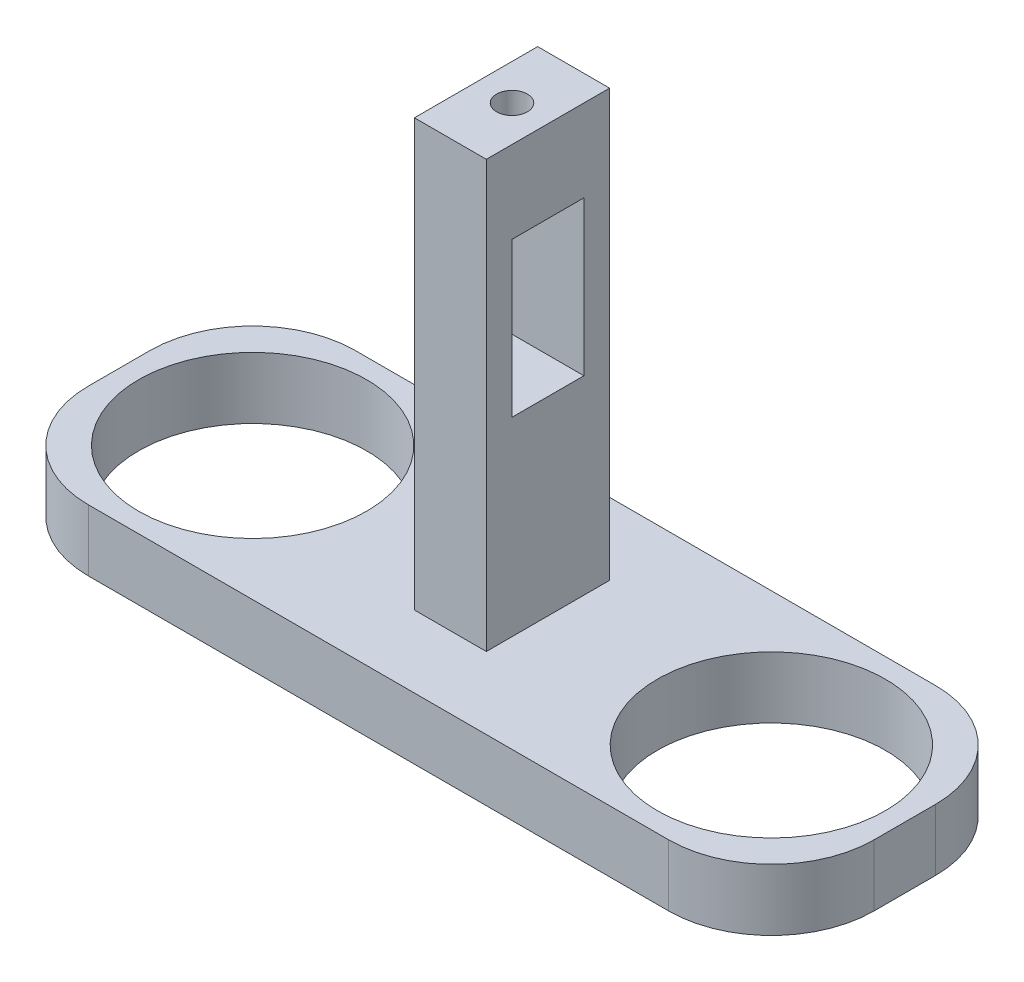
SolidWorks part; units mm, degrees
ref_plane "Front" through (0, 0, 0) normal (0, 0, 1) x (1, 0, 0)
ref_plane "Top" through (0, 0, 0) normal (0, 1, 0) x (1, 0, 0)
ref_plane "Right" through (0, 0, 0) normal (1, 0, 0) x (0, 0, -1)
sketch "Эскиз1" plane through (0, 0, 0) normal (0, 1, 0) x (1, 0, 0)
  line L1 (-20.875, -13) -> (20.875, -13)
  line L2 (-20.875, -13) -> (-20.875, 13)
  line L3 (-20.875, 13) -> (20.875, 13)
  line L4 (20.875, -13) -> (20.875, 13)
  line L5 (-20.875, -13) -> (20.875, 13) construction
  line L6 (-20.875, 13) -> (20.875, -13) construction
  point P0 (0, 0)
  dimension "D1" = 41.75
  dimension "D2" = 26
extrude "Бобышка-Вытянуть1" add sketch "Эскиз1" along normal blind 6
sketch "Эскиз2" plane through (0, 6, 0) normal (0, 1, 0) x (1, 0, 0)
  line L0 (20.875, 0) -> (7.875, 0) construction
  line L1 (20.875, -13) -> (20.875, 13) construction
  circle A0 centre (7.875, 0) radius 11.1
  dimension "D2" = 22.2
  dimension "D1" = 13
extrude "Вырез-Вытянуть1" cut sketch "Эскиз2" against normal blind 6
sketch "Эскиз3" plane through (0, 6, 0) normal (0, 1, 0) x (1, 0, 0)
  line L5 (-20.875, 0) -> (-13.875, 0) construction
  line L6 (-20.875, 13) -> (-20.875, -13) construction
  line L7 (-13.875, -6) -> (-13.875, 6) construction
  line L9 (-13.875, -6) -> (-20.875, -6)
  line L10 (-13.875, -6) -> (-13.875, 6)
  line L11 (-13.875, 6) -> (-20.875, 6)
  line L12 (-20.875, -6) -> (-20.875, 6)
  point P9 (-13.875, 0)
  dimension "D1" = 7
  dimension "D2" = 6
  dimension "D3" = 12
extrude "Бобышка-Вытянуть2" add sketch "Эскиз3" along normal blind 41.5 contours L10 L9 L12 L11
sketch "Эскиз4" plane through (-20.875, 0, 0) normal (-1, 0, 0) x (0, 0, 1)
  line L0 (0, 47.5) -> (0, 39.5) construction
  line L1 (6, 47.5) -> (-6, 47.5) construction
  line L2 (-3.5, 39.5) -> (3.5, 39.5) construction
  line L4 (-3.5, 39.5) -> (3.5, 39.5)
  line L5 (-3.5, 39.5) -> (-3.5, 24.5)
  line L6 (-3.5, 24.5) -> (3.5, 24.5)
  line L7 (3.5, 39.5) -> (3.5, 24.5)
  point P8 (0, 39.5)
  dimension "D1" = 8
  dimension "D2" = 3.5
  dimension "D3" = 7
  dimension "D4" = 15
extrude "Вырез-Вытянуть2" cut sketch "Эскиз4" against normal blind 7
fillet "Скругление1" radius 10 2 edges at (20.875, 3, -13) (20.875, 3, 13)
ref_plane "Плоскость1" through (-17.375, 0, 0) normal (-1, 0, 0) x (0, 0, 1)
mirror "Зеркальное отражение1" about plane through (-17.375, 0, 0) normal (-1, 0, 0) of "Скругление1", "Бобышка-Вытянуть1", "Вырез-Вытянуть1", "Бобышка-Вытянуть2", "Вырез-Вытянуть2"
sketch "Эскиз5" plane through (0, 47.5, 0) normal (0, 1, 0) x (1, 0, 0)
  line L0 (-20.875, 0) -> (-13.875, 0) construction
  line L3 (-20.875, -6) -> (-20.875, 6) construction
  line L4 (-13.875, -6) -> (-13.875, 6) construction
  circle A0 centre (-17.375, 0) radius 1.5
  dimension "D2" = 3
  dimension "D1" = 7
extrude "Вырез-Вытянуть4" cut sketch "Эскиз5" against normal blind 8
